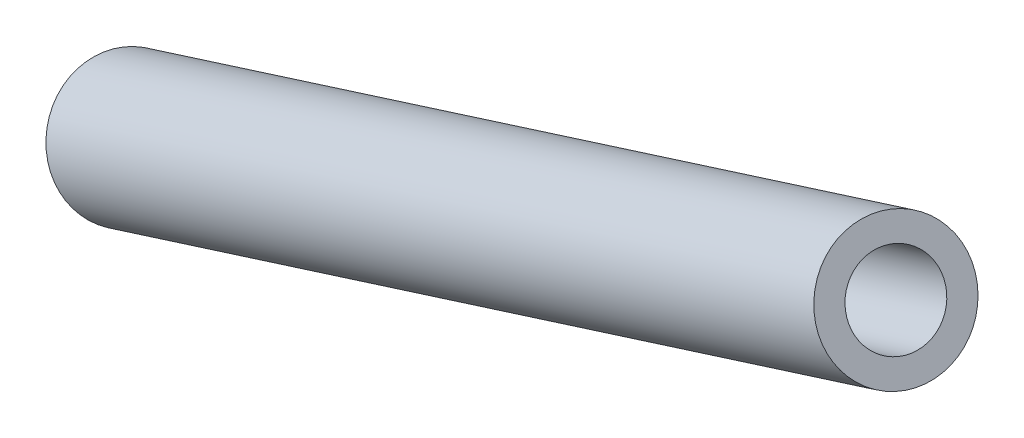
SolidWorks part; units mm, degrees
other "Compression Outer Sleeve"
ref_plane "Front Plane" through (0, 0, 0) normal (0, 0, 1) x (1, 0, 0)
ref_plane "Top Plane" through (0, 0, 0) normal (0, 1, 0) x (1, 0, 0)
ref_plane "Right Plane" through (0, 0, 0) normal (1, 0, 0) x (0, 0, -1)
sketch3d "Sliding sleeve outside sketch datum points"
  point P0 (-34.1193, -76.9152, -2.0974)
  point P1 (-29.1842, -84.5818, -6.2045)
  point P2 (-34.1193, -81.6374, 6.7174)
ref_plane "Sliding sleeve outside sketch plane" through (-55.3357, -27.6774, -14.8272) normal (-0.8697, -0.435, -0.233) x (-0.2084, -0.1043, 0.9725)
sketch "Sliding sleeve outside sketch" plane through (-55.3357, -27.6774, -14.8272) normal (-0.8697, -0.435, -0.233) x (-0.2084, -0.1043, 0.9725)
  circle A0 centre (13.0902, -53.5275) radius 2.5
extrude "Sliding sleeve outside" add sketch "Sliding sleeve outside sketch" along normal blind 46.3649 separate body
sketch3d "Sliding sleeve bore sketch datum points"
  point P0 (-34.0323, -76.8717, -2.0741)
  point P1 (-29.0972, -84.5383, -6.1812)
  point P2 (-34.0323, -81.5939, 6.7407)
ref_plane "Sliding sleeve bore sketch plane" through (-55.2488, -27.6339, -14.8039) normal (-0.8697, -0.435, -0.233) x (-0.2084, -0.1043, 0.9725)
sketch "Sliding sleeve bore sketch" plane through (-55.2488, -27.6339, -14.8039) normal (-0.8697, -0.435, -0.233) x (-0.2084, -0.1043, 0.9725)
  circle A0 centre (13.0902, -53.5275) radius 1.55
extrude "Sliding sleeve bore" cut sketch "Sliding sleeve bore sketch" along normal blind 46.5649
